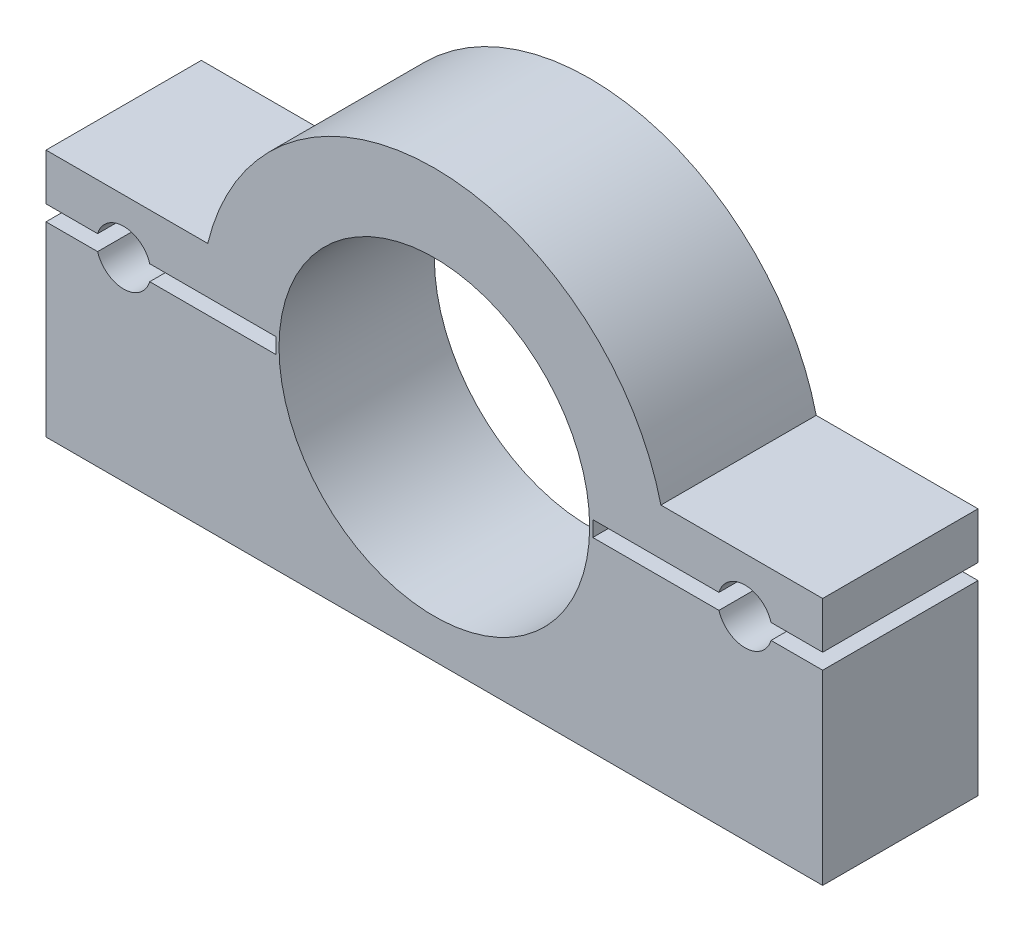
SolidWorks part; units mm, degrees
ref_plane "前视基准面" through (0, 0, 0) normal (0, 0, 1) x (1, 0, 0)
ref_plane "上视基准面" through (0, 0, 0) normal (0, 1, 0) x (1, 0, 0)
ref_plane "右视基准面" through (0, 0, 0) normal (1, 0, 0) x (0, 0, -1)
ref_plane "基准面1" through (0, 0, -10) normal (0, 0, 1) x (1, 0, 0)
sketch "草图6" plane through (0, 0, -10) normal (0, 0, 1) x (1, 0, 0)
  line L0 (-50, 0) -> (50, 0)
  line L1 (50, 0) -> (50, 32)
  line L2 (50, 32) -> (29.1719, 32)
  line L3 (-29.1719, 32) -> (-50, 32)
  line L4 (-50, 32) -> (-50, 0)
  circle A0 centre (0, 25) radius 20
  arc A1 (29.1719, 32) -> (-29.1719, 32) centre (0, 25) ccw
extrude "凸台-拉伸6" add sketch "草图6" along normal blind 20
sketch "草图8" plane through (0, 0, -10) normal (0, 0, 1) x (1, 0, 0)
  line L0 (20.4, 24) -> (51, 24)
  line L1 (51, 24) -> (51, 26)
  line L2 (51, 26) -> (20.4, 26)
  line L3 (20.4, 26) -> (20.4, 24)
  line L4 (-51, 24) -> (-20.4, 24)
  line L5 (-20.4, 24) -> (-20.4, 26)
  line L6 (-20.4, 26) -> (-51, 26)
  line L7 (-51, 26) -> (-51, 24)
extrude "切除-拉伸2" cut sketch "草图8" against normal mid plane 202
sketch "草图9" plane through (0, 0, -10) normal (0, 0, 1) x (1, 0, 0)
  circle A0 centre (-40, 25) radius 3.5
  circle A1 centre (40, 25) radius 3.5
extrude "切除-拉伸3" cut sketch "草图9" along normal through all
